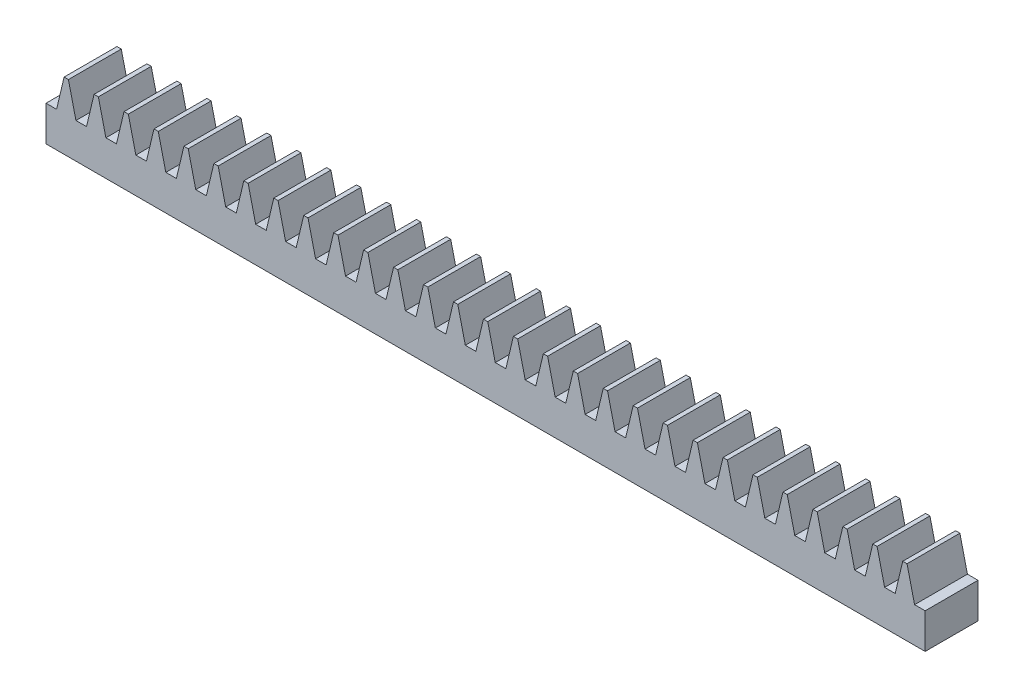
SolidWorks part; units mm, degrees
ref_plane "Front Plane" through (0, 0, 0) normal (0, 0, 1) x (1, 0, 0)
ref_plane "Top Plane" through (0, 0, 0) normal (0, 1, 0) x (1, 0, 0)
ref_plane "Right Plane" through (0, 0, 0) normal (1, 0, 0) x (0, 0, -1)
sketch "Sketch1" plane through (0, 0, 0) normal (0, 0, 1) x (1, 0, 0)
  line L0 (0, 0) -> (52.9003, 0) construction
  line L1 (0, 0) -> (0.3, 0)
  line L2 (24.95, 0) -> (24.95, -1)
  line L3 (0, 0) -> (0, -1)
  line L4 (0.3, 0) -> (0.5139, 0.9)
  line L5 (1.15, 0) -> (1.3639, 0.9)
  line L6 (0.85, 0) -> (1.15, 0)
  line L7 (0.85, 0) -> (0.6361, 0.9)
  line L8 (2, 0) -> (2.2139, 0.9)
  line L9 (1.7, 0) -> (2, 0)
  line L10 (1.7, 0) -> (1.4861, 0.9)
  line L11 (2.85, 0) -> (3.0639, 0.9)
  line L12 (2.55, 0) -> (2.85, 0)
  line L13 (2.55, 0) -> (2.3361, 0.9)
  line L14 (3.7, 0) -> (3.9139, 0.9)
  line L15 (3.4, 0) -> (3.7, 0)
  line L16 (3.4, 0) -> (3.1861, 0.9)
  line L17 (4.55, 0) -> (4.7639, 0.9)
  line L18 (4.25, 0) -> (4.55, 0)
  line L19 (4.25, 0) -> (4.0361, 0.9)
  line L20 (5.4, 0) -> (5.6139, 0.9)
  line L21 (5.1, 0) -> (5.4, 0)
  line L22 (5.1, 0) -> (4.8861, 0.9)
  line L23 (6.25, 0) -> (6.4639, 0.9)
  line L24 (5.95, 0) -> (6.25, 0)
  line L25 (5.95, 0) -> (5.7361, 0.9)
  line L26 (7.1, 0) -> (7.3139, 0.9)
  line L27 (6.8, 0) -> (7.1, 0)
  line L28 (6.8, 0) -> (6.5861, 0.9)
  line L29 (7.95, 0) -> (8.1639, 0.9)
  line L30 (7.65, 0) -> (7.95, 0)
  line L31 (7.65, 0) -> (7.4361, 0.9)
  line L32 (8.8, 0) -> (9.0139, 0.9)
  line L33 (8.5, 0) -> (8.8, 0)
  line L34 (8.5, 0) -> (8.2861, 0.9)
  line L35 (9.65, 0) -> (9.8639, 0.9)
  line L36 (9.35, 0) -> (9.65, 0)
  line L37 (9.35, 0) -> (9.1361, 0.9)
  line L38 (10.5, 0) -> (10.7139, 0.9)
  line L39 (10.2, 0) -> (10.5, 0)
  line L40 (10.2, 0) -> (9.9861, 0.9)
  line L41 (11.35, 0) -> (11.5639, 0.9)
  line L42 (11.05, 0) -> (11.35, 0)
  line L43 (11.05, 0) -> (10.8361, 0.9)
  line L44 (12.2, 0) -> (12.4139, 0.9)
  line L45 (11.9, 0) -> (12.2, 0)
  line L46 (11.9, 0) -> (11.6861, 0.9)
  line L47 (13.05, 0) -> (13.2639, 0.9)
  line L48 (12.75, 0) -> (13.05, 0)
  line L49 (12.75, 0) -> (12.5361, 0.9)
  line L50 (13.9, 0) -> (14.1139, 0.9)
  line L51 (13.6, 0) -> (13.9, 0)
  line L52 (13.6, 0) -> (13.3861, 0.9)
  line L53 (14.75, 0) -> (14.9639, 0.9)
  line L54 (14.45, 0) -> (14.75, 0)
  line L55 (14.45, 0) -> (14.2361, 0.9)
  line L56 (15.6, 0) -> (15.8139, 0.9)
  line L57 (15.3, 0) -> (15.6, 0)
  line L58 (15.3, 0) -> (15.0861, 0.9)
  line L59 (16.45, 0) -> (16.6639, 0.9)
  line L60 (16.15, 0) -> (16.45, 0)
  line L61 (16.15, 0) -> (15.9361, 0.9)
  line L62 (17.3, 0) -> (17.5139, 0.9)
  line L63 (17, 0) -> (17.3, 0)
  line L64 (17, 0) -> (16.7861, 0.9)
  line L65 (18.15, 0) -> (18.3639, 0.9)
  line L66 (17.85, 0) -> (18.15, 0)
  line L67 (17.85, 0) -> (17.6361, 0.9)
  line L68 (19, 0) -> (19.2139, 0.9)
  line L69 (18.7, 0) -> (19, 0)
  line L70 (18.7, 0) -> (18.4861, 0.9)
  line L71 (19.85, 0) -> (20.0639, 0.9)
  line L72 (19.55, 0) -> (19.85, 0)
  line L73 (19.55, 0) -> (19.3361, 0.9)
  line L74 (20.7, 0) -> (20.9139, 0.9)
  line L75 (20.4, 0) -> (20.7, 0)
  line L76 (20.4, 0) -> (20.1861, 0.9)
  line L77 (21.55, 0) -> (21.7639, 0.9)
  line L78 (21.25, 0) -> (21.55, 0)
  line L79 (21.25, 0) -> (21.0361, 0.9)
  line L80 (22.4, 0) -> (22.6139, 0.9)
  line L81 (22.1, 0) -> (22.4, 0)
  line L82 (22.1, 0) -> (21.8861, 0.9)
  line L83 (23.25, 0) -> (23.4639, 0.9)
  line L84 (22.95, 0) -> (23.25, 0)
  line L85 (22.95, 0) -> (22.7361, 0.9)
  line L86 (24.1, 0) -> (24.3139, 0.9)
  line L87 (23.8, 0) -> (24.1, 0)
  line L88 (23.8, 0) -> (23.5861, 0.9)
  line L89 (0, -1) -> (24.95, -1)
  line L90 (24.65, 0) -> (24.95, 0)
  line L91 (24.65, 0) -> (24.4361, 0.9)
  line L92 (0.5139, 0.9) -> (0.6361, 0.9)
  line L93 (24.3139, 0.9) -> (24.4361, 0.9)
  line L94 (23.4639, 0.9) -> (23.5861, 0.9)
  line L95 (22.6139, 0.9) -> (22.7361, 0.9)
  line L96 (21.7639, 0.9) -> (21.8861, 0.9)
  line L97 (20.9139, 0.9) -> (21.0361, 0.9)
  line L98 (20.0639, 0.9) -> (20.1861, 0.9)
  line L99 (19.2139, 0.9) -> (19.3361, 0.9)
  line L100 (18.3639, 0.9) -> (18.4861, 0.9)
  line L101 (17.5139, 0.9) -> (17.6361, 0.9)
  line L102 (16.6639, 0.9) -> (16.7861, 0.9)
  line L103 (15.8139, 0.9) -> (15.9361, 0.9)
  line L104 (14.9639, 0.9) -> (15.0861, 0.9)
  line L105 (14.1139, 0.9) -> (14.2361, 0.9)
  line L106 (13.2639, 0.9) -> (13.3861, 0.9)
  line L107 (12.4139, 0.9) -> (12.5361, 0.9)
  line L108 (11.5639, 0.9) -> (11.6861, 0.9)
  line L109 (10.7139, 0.9) -> (10.8361, 0.9)
  line L110 (9.8639, 0.9) -> (9.9861, 0.9)
  line L111 (9.0139, 0.9) -> (9.1361, 0.9)
  line L112 (8.1639, 0.9) -> (8.2861, 0.9)
  line L113 (7.3139, 0.9) -> (7.4361, 0.9)
  line L114 (6.4639, 0.9) -> (6.5861, 0.9)
  line L115 (5.6139, 0.9) -> (5.7361, 0.9)
  line L116 (4.7639, 0.9) -> (4.8861, 0.9)
  line L117 (3.9139, 0.9) -> (4.0361, 0.9)
  line L118 (3.0639, 0.9) -> (3.1861, 0.9)
  line L119 (2.2139, 0.9) -> (2.3361, 0.9)
  line L120 (1.3639, 0.9) -> (1.4861, 0.9)
  line L121 (24.95, 0) -> (25.1639, 0.9) [skipped]
  dimension "D1" = 0.3
  dimension "D3" = 30
extrude "Boss-Extrude1" add sketch "Sketch1" along normal blind 1.5
